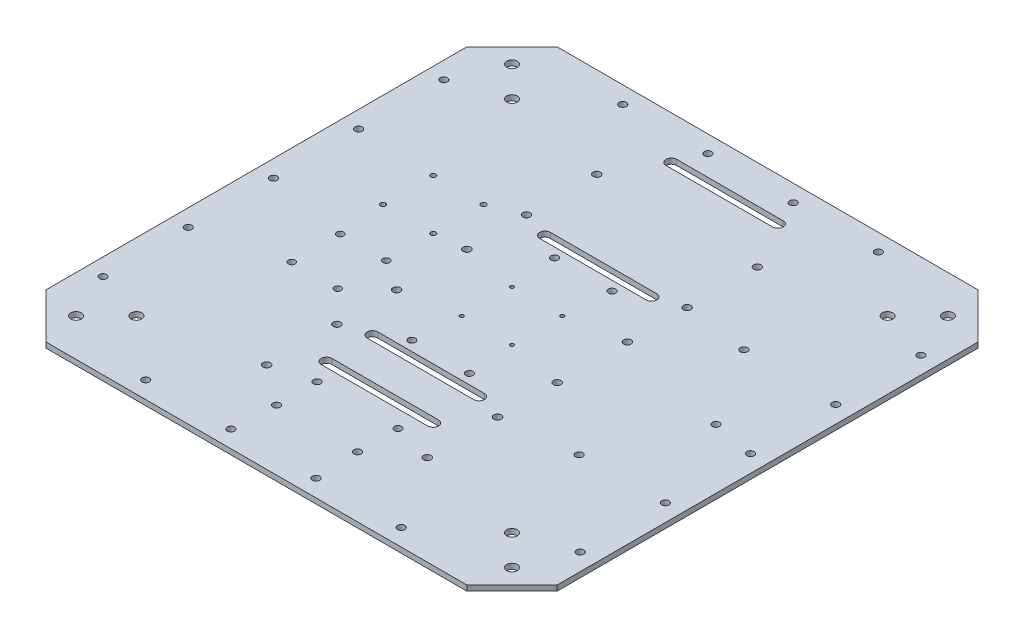
SolidWorks part; units mm, degrees
ref_plane "Front Plane" through (0, 0, 0) normal (0, 0, 1) x (1, 0, 0)
ref_plane "Top Plane" through (0, 0, 0) normal (0, 1, 0) x (1, 0, 0)
ref_plane "Right Plane" through (0, 0, 0) normal (1, 0, 0) x (0, 0, -1)
sketch "Sketch1" plane through (0, 0, 0) normal (0, 1, 0) x (1, 0, 0)
  line L0 (-121.2861, 45.3182) -> (-94.3453, 72.259)
  line L1 (-121.2861, 72.259) -> (183.5139, 72.259)
  line L2 (-121.2861, 72.259) -> (-121.2861, -232.541)
  line L3 (-121.2861, -232.541) -> (183.5139, -232.541)
  line L4 (183.5139, 72.259) -> (183.5139, -232.541)
  line L5 (31.1139, 95.069) -> (31.1139, -294.9418) construction
  line L6 (-146.0448, -80.141) -> (218.038, -80.141) construction
  line L7 (183.5139, 45.3182) -> (156.5732, 72.259)
  line L8 (183.5139, -205.6003) -> (156.5732, -232.541)
  line L9 (-121.2861, -205.6003) -> (-94.3453, -232.541)
  point P8 (31.1139, 72.259)
  point P11 (-121.2861, -80.141)
  dimension "D1" = 304.8
  dimension "D2" = 304.8
  dimension "D3" = 45
  dimension "D4" = 38.1
extrude "Boss-Extrude1" add sketch "Sketch1" along normal blind 3.175
sketch "Sketch2" plane through (0, 3.175, 0) normal (0, 1, 0) x (1, 0, 0)
  line L0 (31.1139, 72.259) -> (31.1139, -287.8465) construction
  line L1 (-94.3453, 72.259) -> (156.5732, 72.259) construction
  line L2 (183.5139, -80.141) -> (-158.2106, -80.141) construction
  line L3 (183.5139, 45.3182) -> (183.5139, -205.6003) construction
  circle A0 centre (13.8419, -37.469) radius 2.159
  circle A1 centre (48.1319, -37.469) radius 2.159
  circle A2 centre (13.8419, -122.559) radius 2.159
  circle A3 centre (48.1319, -122.559) radius 2.159
  dimension "D5" = 4.318
  dimension "D6" = 4.318
  dimension "D7" = 4.318
  dimension "D8" = 4.318
  dimension "D1" = 17.272
  dimension "D2" = 34.29
  dimension "D3" = 85.09
  dimension "D4" = 42.672
extrude "Cut-Extrude1" cut sketch "Sketch2" against normal through all
sketch "Sketch4" plane through (0, 3.175, 0) normal (0, 1, 0) x (1, 0, 0)
  line L0 (-0.6361, 46.644) -> (62.8639, 46.644) construction
  line L1 (-0.6361, 49.819) -> (62.8639, 49.819)
  line L2 (-0.6361, 43.469) -> (62.8639, 43.469)
  line L3 (-0.6361, -28.706) -> (62.8639, -28.706) construction
  line L4 (-0.6361, -25.531) -> (62.8639, -25.531)
  line L5 (-0.6361, -31.881) -> (62.8639, -31.881)
  line L6 (31.1139, 72.259) -> (31.1139, -65.9651) construction
  line L7 (-94.3453, 72.259) -> (156.5732, 72.259) construction
  line L8 (-121.2861, -80.141) -> (257.7387, -80.141) construction
  line L9 (-121.2861, 45.3182) -> (-121.2861, -205.6003) construction
  line L10 (31.1139, -232.541) -> (31.1139, -94.317) construction
  line L11 (-0.6361, -131.576) -> (62.8639, -131.576) construction
  line L12 (-0.6361, -128.401) -> (62.8639, -128.401)
  line L13 (-0.6361, -134.751) -> (62.8639, -134.751)
  line L14 (-0.6361, -158.926) -> (62.8639, -158.926) construction
  line L15 (-0.6361, -155.751) -> (62.8639, -155.751)
  line L16 (-0.6361, -162.101) -> (62.8639, -162.101)
  arc A0 (-0.6361, 49.819) -> (-0.6361, 43.469) centre (-0.6361, 46.644) ccw
  arc A1 (62.8639, 43.469) -> (62.8639, 49.819) centre (62.8639, 46.644) ccw
  arc A2 (-0.6361, -25.531) -> (-0.6361, -31.881) centre (-0.6361, -28.706) ccw
  arc A3 (62.8639, -31.881) -> (62.8639, -25.531) centre (62.8639, -28.706) ccw
  arc A5 (-0.6361, -128.401) -> (-0.6361, -134.751) centre (-0.6361, -131.576) ccw
  arc A6 (62.8639, -134.751) -> (62.8639, -128.401) centre (62.8639, -131.576) ccw
  arc A7 (-0.6361, -155.751) -> (-0.6361, -162.101) centre (-0.6361, -158.926) ccw
  arc A8 (62.8639, -162.101) -> (62.8639, -155.751) centre (62.8639, -158.926) ccw
  point P2 (31.1139, 46.644)
  point P7 (31.1139, -28.706)
  point P28 (31.1139, -131.576)
  point P33 (31.1139, -158.926)
  point P40 (0, 0)
  point P41 (0, 0)
  point P42 (0, 0)
  point P43 (0, 0)
  dimension "D1" = 63.5
  dimension "D2" = 63.5
  dimension "D3" = 6.35
  dimension "D4" = 6.35
  dimension "D5" = 69
  dimension "D6" = 48.26
  dimension "D7" = 63.5
  dimension "D8" = 63.5
  dimension "D9" = 6.35
  dimension "D10" = 6.35
  dimension "D11" = 21
  dimension "D12" = 48.26
extrude "Cut-Extrude2" cut sketch "Sketch4" against normal through all
sketch "Sketch7" plane through (0, 3.175, 0) normal (0, 1, 0) x (1, 0, 0)
  line L0 (-49.9121, 57.7696) -> (-49.9121, -55.8318) construction
  line L1 (-121.2861, -80.141) -> (183.5139, -80.141) construction
  line L2 (-121.2861, 45.3182) -> (-121.2861, -205.6003) construction
  line L3 (183.5139, 45.3182) -> (183.5139, -205.6003) construction
  line L4 (31.1139, 72.259) -> (31.1139, -252.674) construction
  line L5 (-94.3453, 72.259) -> (156.5732, 72.259) construction
  circle A0 centre (-34.9261, -31.119) radius 1.524
  circle A1 centre (-34.9261, -61.091) radius 1.524
  circle A2 centre (-64.8981, -61.091) radius 1.524
  circle A3 centre (-64.8981, -31.119) radius 1.524
  dimension "D1" = 3.048
  dimension "D2" = 14.986
  dimension "D4" = 29.972
  dimension "D3" = 3.048
  dimension "D5" = 19.05
  dimension "D6" = 66.04
  dimension "D7" = 14.986
extrude "Cut-Extrude3" cut sketch "Sketch7" against normal through all
sketch "Sketch8" plane through (0, 3.175, 0) normal (0, 1, 0) x (1, 0, 0)
  line L0 (-94.3453, -232.541) -> (156.5732, -232.541) construction
  line L1 (183.5139, 45.3182) -> (183.5139, -205.6003) construction
  circle A0 centre (73.0239, -207.649) radius 1.524
  circle A1 centre (73.0239, -177.169) radius 1.524
  circle A2 centre (96.8999, -207.649) radius 1.524
  circle A3 centre (96.8999, -177.169) radius 1.524
  dimension "D1" = 3.048
  dimension "D2" = 30.48
  dimension "D3" = 23.876
  dimension "D4" = 24.892
  dimension "D5" = 86.614
extrude "Cut-Extrude4" [suppressed] cut sketch "Sketch8" against normal through all and the other way through all
sketch "Sketch10" plane through (0, 0, 0) normal (0, -1, 0) x (1, 0, 0)
  line L0 (-94.3453, 232.541) -> (156.5732, 232.541) construction
  line L1 (31.1139, 232.541) -> (31.1139, 128.7119) construction
  line L2 (-0.6361, 162.101) -> (62.8639, 162.101) construction
  circle A0 centre (6.9839, 196.391) radius 2.159
  circle A1 centre (55.2439, 196.391) radius 2.159
  circle A2 centre (6.9839, 172.261) radius 2.159
  circle A3 centre (55.2439, 172.261) radius 2.159
  dimension "D1" = 4.318
  dimension "D2" = 48.26
  dimension "D4" = 10.16
  dimension "D6" = 4.318
  dimension "D7" = 4.318
  dimension "D8" = 4.318
  dimension "D3" = 24.13
  dimension "D5" = 24.13
extrude "Cut-Extrude6" cut sketch "Sketch10" against normal through all
sketch "Sketch9" plane through (0, 0, 0) normal (0, -1, 0) x (-1, 0, 0)
  line L1 (121.2861, -80.141) -> (-327.4314, -80.141) construction
  line L2 (48.6421, -47.3693) -> (48.6421, -130.2963) construction
  line L3 (-31.1139, 72.259) -> (-31.1139, -331.7119) construction
  line L4 (94.3453, 72.259) -> (-156.5732, 72.259) construction
  line L7 (121.2861, 45.3182) -> (121.2861, -205.6003) construction
  circle A0 centre (62.3581, -117.987) radius 2.032
  circle A1 centre (34.9261, -117.987) radius 2.032
  circle A2 centre (62.3581, -89.031) radius 2.032
  circle A3 centre (34.9261, -89.031) radius 2.032
  dimension "D1" = 4.064
  dimension "D9" = 4.064
  dimension "D2" = 66.04
  dimension "D3" = 28.956
  dimension "D4" = 8.89
  dimension "D8" = 13.716
extrude "Cut-Extrude5" cut sketch "Sketch9" against normal through all
sketch "Sketch13" plane through (0, 0, 0) normal (0, -1, 0) x (1, 0, 0)
  line L0 (31.1139, -72.259) -> (31.1139, 261.4711) construction
  line L1 (-94.3453, -72.259) -> (156.5732, -72.259) construction
  line L2 (-121.2861, 80.141) -> (239.2508, 80.141) construction
  line L3 (-121.2861, -45.3182) -> (-121.2861, 205.6003) construction
  circle A0 centre (16.1139, 95.141) radius 1.1
  circle A1 centre (16.1139, 65.141) radius 1.1
  circle A2 centre (46.1139, 65.141) radius 1.1
  circle A3 centre (46.1139, 95.141) radius 1.1
  point P16 (0, 0)
  point P17 (0, 0)
  point P18 (0, 0)
  point P19 (0, 0)
  dimension "D1" = 2.2
  dimension "D2" = 2.2
  dimension "D3" = 30
  dimension "D4" = 15
  dimension "D5" = 15
extrude "Cut-Extrude8" cut sketch "Sketch13" against normal through all
sketch "Sketch14" plane through (0, 0, 0) normal (0, -1, 0) x (1, 0, 0)
  line L0 (31.1139, 232.541) -> (31.1139, -154.5354) construction
  line L1 (-94.3453, 232.541) -> (156.5732, 232.541) construction
  line L2 (-121.2861, 80.141) -> (331.9066, 80.141) construction
  line L3 (-121.2861, -45.3182) -> (-121.2861, 205.6003) construction
  line L4 (-121.2861, 205.6003) -> (-94.3453, 232.541) construction
  line L5 (-224.559, -175.5319) -> (286.7869, 335.814) construction
  line L6 (-224.559, -175.5319) -> (286.7869, -175.5319) construction
  line L7 (-224.559, -175.5319) -> (-224.559, 335.814) construction
  line L8 (-121.2861, 205.6003) -> (-94.3453, 232.541) construction
  line L9 (-107.8157, 219.0706) -> (-48.5429, 159.7979) construction
  line L10 (-224.559, 335.814) -> (286.7869, 335.814) construction
  line L11 (286.7869, -175.5319) -> (286.7869, 335.814) construction
  line L12 (286.7869, -175.5319) -> (-224.559, 335.814) construction
  line L14 (-121.2861, -45.3182) -> (-94.3453, -72.259) construction
  line L21 (-224.559, -175.5319) -> (-107.8157, -58.7886) construction
  line L22 (170.0436, -58.7886) -> (286.7869, -175.5319) construction
  line L23 (183.5139, -45.3182) -> (156.5732, -72.259) construction
  line L24 (170.0436, 219.0706) -> (286.7869, 335.814) construction
  line L25 (183.5139, 205.6003) -> (156.5732, 232.541) construction
  line L26 (-224.559, 335.814) -> (-107.8157, 219.0706) construction
  circle A1 centre (-98.8354, 210.0904) radius 3.175
  circle A3 centre (-80.8749, 192.1299) radius 3.175
  circle A4 centre (143.1028, 192.1299) radius 3.175
  circle A7 centre (161.0633, 210.0904) radius 3.175
  circle A8 centre (-98.8354, -49.8083) radius 3.175
  circle A11 centre (-80.8749, -31.8478) radius 3.175
  circle A14 centre (161.0633, -49.8083) radius 3.175
  circle A15 centre (143.1028, -31.8478) radius 3.175
  point P8 (31.1139, 80.141)
  point P30 (286.7869, 80.141)
  point P33 (-107.8157, -58.7886)
  point P36 (31.1139, -175.5319)
  point P45 (0, 0)
  dimension "D3" = 6.35
  dimension "D6" = 6.35
  dimension "D1" = 12.7
  dimension "D2" = 165.1
  dimension "D9" = 25.4
extrude "Cut-Extrude9" cut sketch "Sketch14" against normal through all
sketch "Sketch15" plane through (0, 0, 0) normal (0, -1, 0) x (1, 0, 0)
  line L0 (31.1139, 232.541) -> (31.1139, 125.875) construction
  line L1 (-94.3453, 232.541) -> (156.5732, 232.541) construction
  line L2 (-121.2861, 80.141) -> (75.4631, 80.141) construction
  line L3 (-121.2861, -45.3182) -> (-121.2861, 205.6003) construction
  circle A0 centre (5.7139, 222.381) radius 2.159
  circle A1 centre (-45.0861, 222.381) radius 2.159
  circle A2 centre (-111.1261, 80.141) radius 2.159
  circle A3 centre (-111.1261, 130.941) radius 2.159
  circle A4 centre (-111.1261, 181.741) radius 2.159
  circle A5 centre (173.3539, 181.741) radius 2.159
  circle A6 centre (173.3539, 130.941) radius 2.159
  circle A7 centre (173.3539, 80.141) radius 2.159
  circle A8 centre (107.3139, 222.381) radius 2.159
  circle A9 centre (56.5139, 222.381) radius 2.159
  circle A10 centre (56.5139, -62.099) radius 2.159
  circle A11 centre (107.3139, -62.099) radius 2.159
  circle A12 centre (173.3539, 29.341) radius 2.159
  circle A13 centre (173.3539, -21.459) radius 2.159
  circle A14 centre (-111.1261, -21.459) radius 2.159
  circle A15 centre (-111.1261, 29.341) radius 2.159
  circle A16 centre (-45.0861, -62.099) radius 2.159
  circle A17 centre (5.7139, -62.099) radius 2.159
  dimension "D3" = 4.318
  dimension "D4" = 4.318
  dimension "D8" = 4.318
  dimension "D9" = 4.318
  dimension "D10" = 4.318
  dimension "D1" = 25.4
  dimension "D2" = 50.8
  dimension "D5" = 10.16
  dimension "D6" = 50.8
  dimension "D7" = 50.8
  dimension "D11" = 10.16
extrude "Cut-Extrude10" cut sketch "Sketch15" against normal through all
sketch "Sketch16" plane through (0, 0, 0) normal (0, -1, 0) x (-1, 0, 0)
  line L0 (-31.1139, 72.259) -> (-31.1139, -323.0503) construction
  line L1 (-97.4079, -121.924) -> (-138.0479, -121.924)
  line L2 (-97.4079, -121.924) -> (-97.4079, -38.358)
  line L3 (-97.4079, -38.358) -> (-138.0479, -38.358)
  line L4 (-138.0479, -121.924) -> (-138.0479, -38.358)
  line L6 (94.3453, 72.259) -> (-156.5732, 72.259) construction
  line L7 (121.2861, -80.141) -> (-312.3855, -80.141) construction
  line L8 (121.2861, 45.3182) -> (121.2861, -205.6003) construction
  circle A0 centre (-122.8079, -131.83) radius 2.159
  circle A1 centre (-117.7279, -28.452) radius 2.159
  circle A2 centre (-147.9539, -75.274) radius 2.159
  point P18 (-138.0479, -80.141)
  point P19 (0, 0)
  dimension "D3" = 9.906
  dimension "D4" = 9.906
  dimension "D5" = 9.906
  dimension "D6" = 15.24
  dimension "D7" = 20.32
  dimension "D8" = 46.65
  dimension "D9" = 4.318
  dimension "D10" = 4.318
  dimension "D11" = 4.318
  dimension "D1" = 83.566
  dimension "D2" = 40.64
  dimension "D12" = 116.84
  dimension "D13" = 0
extrude "Cut-Extrude11" cut sketch "Sketch16" against normal through all contours A2 | A0 | A1
sketch "Sketch17" plane through (0, 3.175, 0) normal (0, 1, 0) x (1, 0, 0)
  line L2 (31.1139, 72.259) -> (31.1139, -395.818) construction
  line L3 (-94.3453, 72.259) -> (156.5732, 72.259) construction
  line L4 (183.5139, -80.141) -> (-127.1454, -80.141) construction
  line L5 (183.5139, 45.3182) -> (183.5139, -205.6003) construction
  circle A12 centre (78.9929, -178.566) radius 2.2225
  circle A13 centre (-16.7651, -178.566) radius 2.2225
  circle A14 centre (78.9929, -136.656) radius 2.2225
  circle A15 centre (-16.7651, -136.656) radius 2.2225
  circle A16 centre (78.9929, -101.096) radius 2.2225
  circle A17 centre (-16.7651, -101.096) radius 2.2225
  circle A18 centre (78.9929, -59.186) radius 2.2225
  circle A19 centre (-16.7651, -59.186) radius 2.2225
  circle A20 centre (78.9929, -23.626) radius 2.2225
  circle A21 centre (-16.7651, -23.626) radius 2.2225
  circle A22 centre (78.9929, 18.284) radius 2.2225
  circle A23 centre (-16.7651, 18.284) radius 2.2225
  circle A24 centre (-16.7651, 18.284) radius 2.2225
  circle A25 centre (78.9929, 18.284) radius 2.2225
  circle A26 centre (-16.7651, -23.626) radius 2.2225
  circle A27 centre (78.9929, -23.626) radius 2.2225
  circle A28 centre (-16.7651, -59.186) radius 2.2225
  circle A29 centre (78.9929, -59.186) radius 2.2225
  circle A30 centre (-16.7651, -101.096) radius 2.2225
  circle A31 centre (78.9929, -101.096) radius 2.2225
  circle A32 centre (-16.7651, -136.656) radius 2.2225
  circle A33 centre (78.9929, -136.656) radius 2.2225
  circle A34 centre (-16.7651, -178.566) radius 2.2225
  point P17 (0, 0)
  point P19 (0, 0)
  point P21 (0, 0)
  point P23 (0, 0)
  dimension "D1" = 4.445
  dimension "D2" = 4.445
  dimension "D3" = 4.445
  dimension "D4" = 4.445
  dimension "D5" = 4.445
  dimension "D6" = 4.445
  dimension "D7" = 4.445
  dimension "D8" = 4.445
  dimension "D9" = 4.445
  dimension "D10" = 4.445
  dimension "D11" = 4.445
  dimension "D12" = 4.445
  dimension "D25" = 56.515
  dimension "D24" = 56.515
  dimension "D13" = 95.758
  dimension "D14" = 41.91
  dimension "D15" = 95.758
  dimension "D16" = 41.91
  dimension "D17" = 95.758
  dimension "D18" = 41.91
  dimension "D19" = 47.879
  dimension "D20" = 47.879
  dimension "D21" = 47.879
  dimension "D22" = 20.955
extrude "Cut-Extrude13" cut sketch "Sketch17" against normal through all contours A23 | A22 | A20 | A21 | A18 | A19 | A17 | A16 | A12 | A14 | A15 | A13
